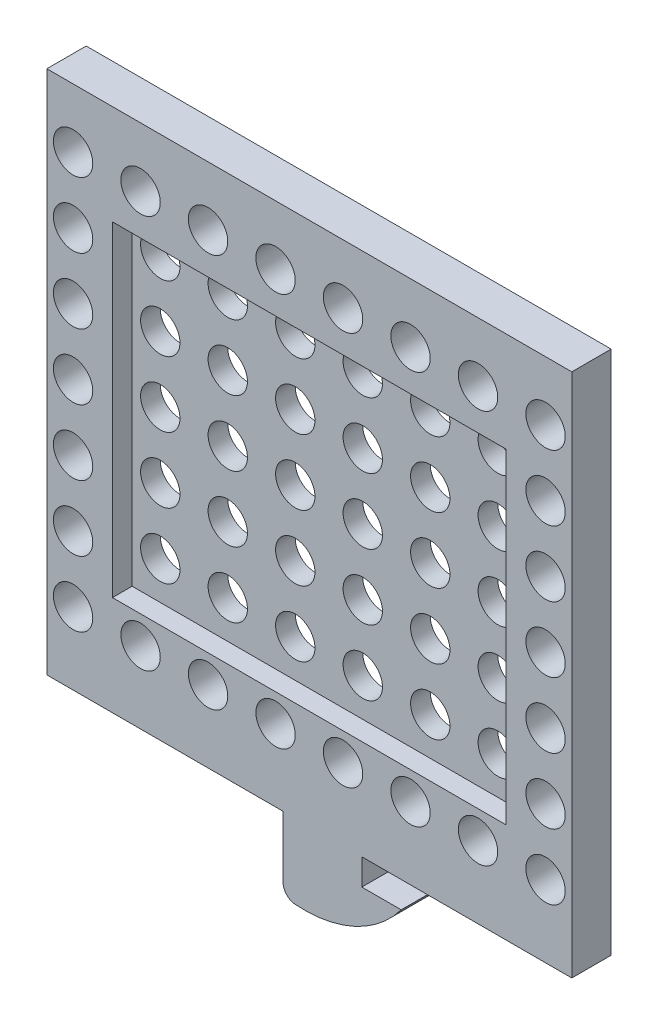
SolidWorks part; units mm, degrees
ref_plane "Plan de face" through (0, 0, 0) normal (0, 0, 1) x (1, 0, 0)
ref_plane "Plan de dessus" through (0, 0, 0) normal (0, 1, 0) x (1, 0, 0)
ref_plane "Plan de droite" through (0, 0, 0) normal (1, 0, 0) x (0, 0, -1)
sketch "Esquisse1" plane through (0, 0, 0) normal (0, 0, 1) x (1, 0, 0)
  line L0 (-18, 2) -> (0, 2)
  line L2 (22, 2) -> (22, 42)
  line L3 (22, 42) -> (-18, 42)
  line L5 (22, 2) -> (-18, 42) construction
  line L6 (22, 42) -> (-18, 2) construction
  line L7 (22, 2) -> (6, 2)
  line L8 (6, 2) -> (6, 0)
  line L9 (0, 2) -> (0, 0)
  line L11 (6, 0) -> (9, 0)
  line L16 (-18, 42) -> (-18, 2)
  line L17 (0, -3.5632) -> (0, 0)
  arc A2 (9, 0) -> (0, -3.5632) centre (1.6147, 5.5061) cw
  dimension "D1" = 40
  dimension "D2" = 40
  dimension "D3" = 2
  dimension "D4" = 2
  dimension "D6" = 3
  dimension "D7" = 18
  dimension "D8" = 16
extrude "Boss.-Extru.1" add sketch "Esquisse1" along normal blind 3
sketch "Esquisse2" plane through (0, 0, 3) normal (0, 0, 1) x (1, 0, 0)
  line L1 (22, 2) -> (22, 42) construction
  circle A0 centre (-16, 37.4899) radius 1.5
  circle A1 centre (-10.8571, 37.4899) radius 1.5
  circle A2 centre (-5.7143, 37.4899) radius 1.5
  circle A3 centre (-0.5714, 37.4899) radius 1.5
  circle A4 centre (4.5714, 37.4899) radius 1.5
  circle A5 centre (9.7143, 37.4899) radius 1.5
  circle A6 centre (14.8571, 37.4899) radius 1.5
  circle A7 centre (20, 37.4899) radius 1.5
  circle A8 centre (-10.8571, 32.4899) radius 1.5
  circle A9 centre (-5.7143, 32.4899) radius 1.5
  circle A10 centre (-0.5714, 32.4899) radius 1.5
  circle A11 centre (4.5714, 32.4899) radius 1.5
  circle A12 centre (9.7143, 32.4899) radius 1.5
  circle A13 centre (14.8571, 32.4899) radius 1.5
  circle A14 centre (-10.8571, 27.4899) radius 1.5
  circle A15 centre (-5.7143, 27.4899) radius 1.5
  circle A16 centre (-0.5714, 27.4899) radius 1.5
  circle A17 centre (4.5714, 27.4899) radius 1.5
  circle A18 centre (9.7143, 27.4899) radius 1.5
  circle A19 centre (14.8571, 27.4899) radius 1.5
  circle A20 centre (-10.8571, 22.4899) radius 1.5
  circle A21 centre (-5.7143, 22.4899) radius 1.5
  circle A22 centre (-0.5714, 22.4899) radius 1.5
  circle A23 centre (4.5714, 22.4899) radius 1.5
  circle A24 centre (9.7143, 22.4899) radius 1.5
  circle A25 centre (14.8571, 22.4899) radius 1.5
  circle A26 centre (-10.8571, 17.4899) radius 1.5
  circle A27 centre (-5.7143, 17.4899) radius 1.5
  circle A28 centre (-0.5714, 17.4899) radius 1.5
  circle A29 centre (4.5714, 17.4899) radius 1.5
  circle A30 centre (9.7143, 17.4899) radius 1.5
  circle A31 centre (14.8571, 17.4899) radius 1.5
  circle A32 centre (-10.8571, 12.4899) radius 1.5
  circle A33 centre (-5.7143, 12.4899) radius 1.5
  circle A34 centre (-0.5714, 12.4899) radius 1.5
  circle A35 centre (4.5714, 12.4899) radius 1.5
  circle A36 centre (9.7143, 12.4899) radius 1.5
  circle A37 centre (14.8571, 12.4899) radius 1.5
  circle A38 centre (-10.8571, 7.4899) radius 1.5
  circle A39 centre (-5.7143, 7.4899) radius 1.5
  circle A40 centre (-0.5714, 7.4899) radius 1.5
  circle A41 centre (4.5714, 7.4899) radius 1.5
  circle A42 centre (9.7143, 7.4899) radius 1.5
  circle A43 centre (14.8571, 7.4899) radius 1.5
  circle A44 centre (-16, 32.4899) radius 1.5
  circle A45 centre (-16, 27.4899) radius 1.5
  circle A46 centre (-16, 22.4899) radius 1.5
  circle A47 centre (-16, 17.4899) radius 1.5
  circle A48 centre (-16, 12.4899) radius 1.5
  circle A49 centre (-16, 7.4899) radius 1.5
  circle A50 centre (20, 32.4899) radius 1.5
  circle A51 centre (20, 27.4899) radius 1.5
  circle A52 centre (20, 22.4899) radius 1.5
  circle A53 centre (20, 17.4899) radius 1.5
  circle A54 centre (20, 12.4899) radius 1.5
  circle A55 centre (20, 7.4899) radius 1.5
  dimension "D1" = 8
  dimension "D2" = 3
  dimension "D4" = 2
  dimension "D5" = 7
  dimension "D6" = 7
  dimension "D7" = 7
extrude "Enlèv. mat.-Extru.1" cut sketch "Esquisse2" against normal through all
sketch "Esquisse4" plane through (0, 0, 3) normal (0, 0, 1) x (1, 0, 0)
  line L1 (17, 9.6016) -> (-13, 9.6016)
  line L2 (17, 9.6016) -> (17, 34.3984)
  line L3 (17, 34.3984) -> (-13, 34.3984)
  line L4 (-13, 9.6016) -> (-13, 34.3984)
  line L5 (17, 9.6016) -> (-13, 34.3984) construction
  line L6 (17, 34.3984) -> (-13, 9.6016) construction
  line L8 (22, 2) -> (22, 42) construction
  point P0 (2, 22)
  point P9 (0, 0)
  dimension "D2" = 5
extrude "Enlèv. mat.-Extru.3" cut sketch "Esquisse4" against normal blind 1.5
fillet "Congé2" radius 1 1 edges at (0, -3.5632, 1.5)
